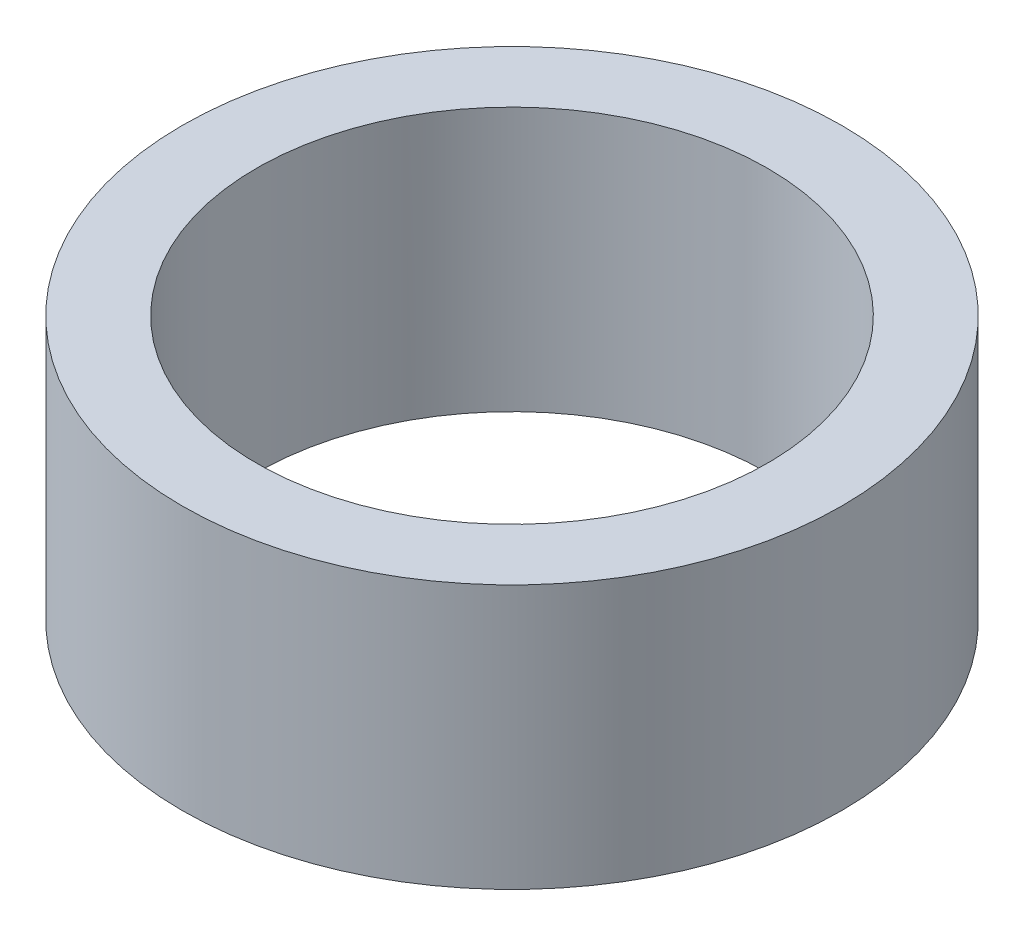
SolidWorks part; units mm, degrees
ref_plane "Front Plane" through (0, 0, 0) normal (0, 0, 1) x (1, 0, 0)
ref_plane "Top Plane" through (0, 0, 0) normal (0, 1, 0) x (1, 0, 0)
ref_plane "Right Plane" through (0, 0, 0) normal (1, 0, 0) x (0, 0, -1)
sketch "Sketch1" plane through (0, 0, 0) normal (0, 1, 0) x (1, 0, 0)
  arc A0 (-7.75, 0) -> (7.75, 0) centre (0, 0) cw
  arc A1 (-10, 0) -> (10, 0) centre (0, 0) cw
  circle A2 centre (0, 0) radius 10
  arc A3 (-7.75, 0) -> (7.75, 0) centre (0, 0) ccw
  dimension "D1" = 7.75
  dimension "D2" = 10
  dimension "D3" = 7.75
  dimension "D4" = 20
extrude "Boss-Extrude1" add sketch "Sketch1" along normal blind 8 contours A2 | A0 A3
